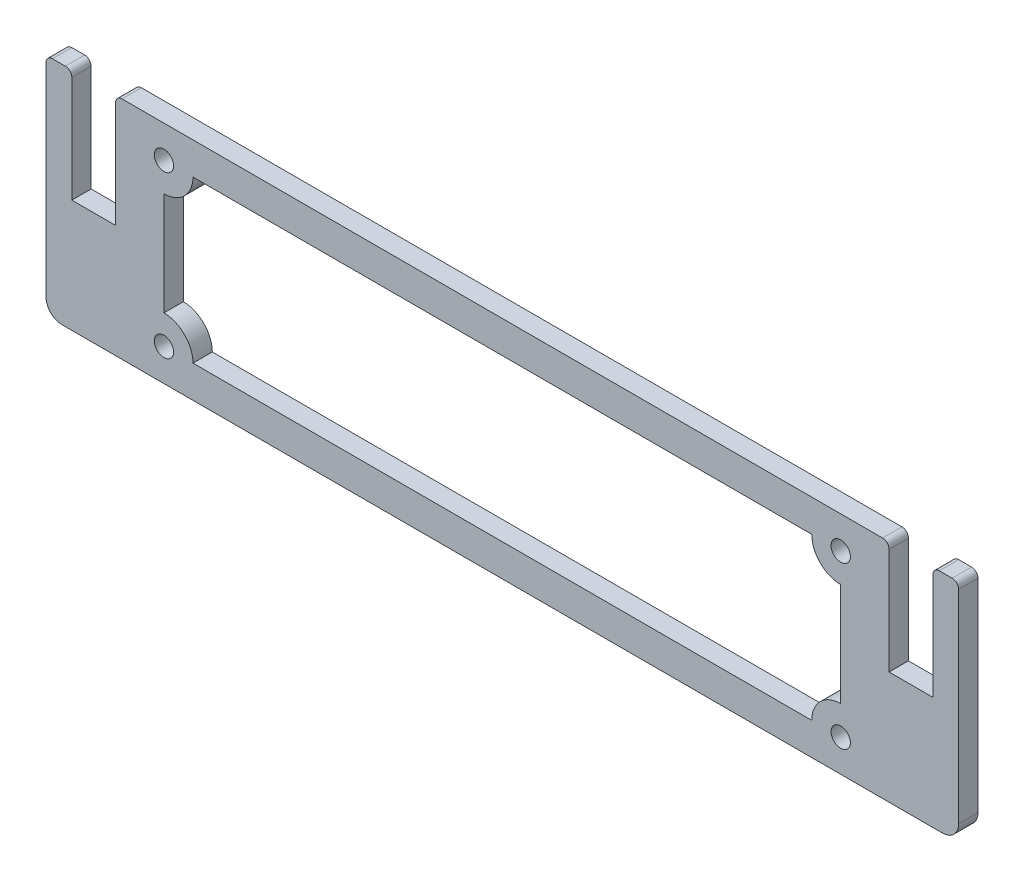
SolidWorks part; units mm, degrees
ref_plane "Спереди" through (0, 0, 0) normal (0, 0, 1) x (1, 0, 0)
ref_plane "Сверху" through (0, 0, 0) normal (0, 1, 0) x (1, 0, 0)
ref_plane "Справа" through (0, 0, 0) normal (1, 0, 0) x (0, 0, -1)
sketch "Эскиз1" plane through (0, 0, 0) normal (0, 0, 1) x (1, 0, 0)
  line L0 (55, 0) -> (-55, 0) construction
  line L1 (-60, -17.5) -> (60, -17.5)
  line L2 (-60, -17.5) -> (-60, 17.5)
  line L3 (-60, 17.5) -> (60, 17.5)
  line L4 (60, -17.5) -> (60, 17.5)
  line L5 (-60, -17.5) -> (60, 17.5) construction
  line L6 (-60, 17.5) -> (60, -17.5) construction
  line L7 (-52.5, -12.5) -> (52.5, -12.5)
  line L8 (-52.5, -12.5) -> (-52.5, 12.5)
  line L9 (-52.5, 12.5) -> (52.5, 12.5)
  line L10 (52.5, -12.5) -> (52.5, 12.5)
  line L11 (-52.5, -12.5) -> (52.5, 12.5) construction
  line L12 (-52.5, 12.5) -> (52.5, -12.5) construction
  line L13 (0, -55) -> (0, 55) construction
  line L14 (-70.8, -17.5) -> (-70.8, 17.5)
  line L15 (60, -17.5) -> (66.8, -17.5)
  line L16 (60, -17.5) -> (60, 0)
  line L17 (60, 0) -> (66.8, 0)
  line L18 (66.8, -17.5) -> (66.8, 0)
  line L19 (66.8, -17.5) -> (70.8, -17.5)
  line L20 (66.8, -17.5) -> (66.8, 17.5)
  line L21 (66.8, 17.5) -> (70.8, 17.5)
  line L22 (70.8, -17.5) -> (70.8, 17.5)
  line L23 (-66.8, -17.5) -> (-66.8, 17.5)
  line L24 (-66.8, 17.5) -> (-70.8, 17.5)
  line L25 (-66.8, -17.5) -> (-70.8, -17.5)
  line L26 (-66.8, -17.5) -> (-66.8, 0)
  line L27 (-60, 0) -> (-66.8, 0)
  line L28 (-60, -17.5) -> (-60, 0)
  line L29 (-60, -17.5) -> (-66.8, -17.5)
  circle A0 centre (52.5, 12.5) radius 1.5
  circle A2 centre (52.5, 12.5) radius 4.5
  circle A3 centre (52.5, -12.5) radius 4.5
  circle A4 centre (52.5, -12.5) radius 1.5
  circle A5 centre (-52.5, -12.5) radius 1.5
  circle A6 centre (-52.5, -12.5) radius 4.5
  circle A7 centre (-52.5, 12.5) radius 4.5
  circle A8 centre (-52.5, 12.5) radius 1.5
  point P0 (0, 0)
  point P6 (0, 0)
  dimension "D5" = 3
  dimension "D1" = 120
  dimension "D2" = 25
  dimension "D3" = 5
  dimension "D4" = 7.5
  dimension "D7" = 6.8
  dimension "D9" = 4
  dimension "D6" = 3
extrude "Бобышка-Вытянуть1" add sketch "Эскиз1" along normal blind 3 contours L25 L23 L24 L14 | L29 L2 L27 L23 | L1 L4 L3 L2 L8 A7 L9 A2 L10 A3 L7 A6 | L15 L18 L17 L4 | L19 L22 L21 L20 L18 | L9 A2 L10 A0 | L10 A2 L9 A0 | L10 A4 L7 A3 | L7 A4 L10 A3 | L8 A6 L7 A5 | L7 A6 L8 A5 | L8 A8 L9 A7 | L9 A8 L8 A7
fillet "Скругление1" radius 2.5 2 edges at (70.8, -17.5, 1.5) (-70.8, -17.5, 1.5)
fillet "Скругление2" radius 1 6 edges at (70.8, 17.5, 1.5) (66.8, 17.5, 1.5) (60, 17.5, 1.5) (-70.8, 17.5, 1.5) (-66.8, 17.5, 1.5) (-60, 17.5, 1.5)
